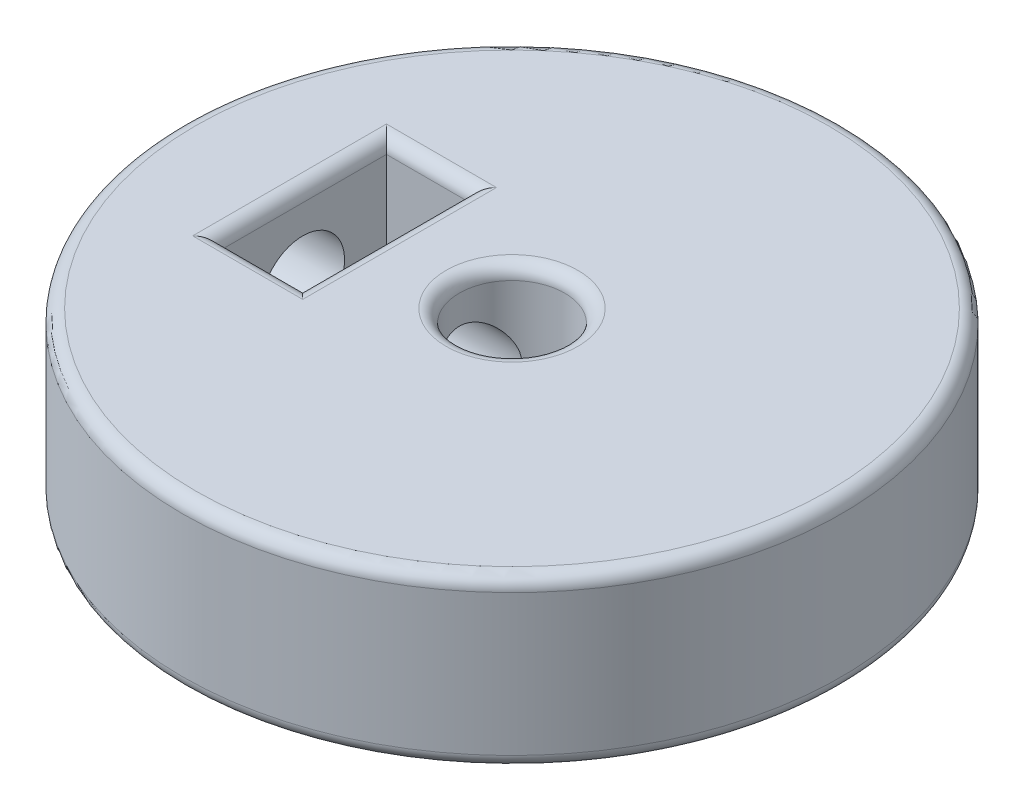
SolidWorks part; units mm, degrees
ref_plane "Front Plane" through (0, 0, 0) normal (0, 0, 1) x (1, 0, 0)
ref_plane "Top Plane" through (0, 0, 0) normal (0, 1, 0) x (1, 0, 0)
ref_plane "Right Plane" through (0, 0, 0) normal (1, 0, 0) x (0, 0, -1)
sketch "Sketch1" plane through (0, 0, 0) normal (0, 1, 0) x (1, 0, 0)
  circle A0 centre (0, 0) radius 4
  circle A1 centre (0, 0) radius 25
  dimension "D1" = 8
  dimension "D2" = 50
extrude "Boss-Extrude1" add sketch "Sketch1" along normal blind 12.7
sketch "Sketch2" plane through (0, 12.7, 0) normal (0, 1, 0) x (1, 0, 0)
  line L1 (-15.875, 6.35) -> (-9.525, 6.35)
  line L2 (-15.875, 6.35) -> (-15.875, -6.35)
  line L3 (-15.875, -6.35) -> (-9.525, -6.35)
  line L4 (-9.525, 6.35) -> (-9.525, -6.35)
  line L5 (-15.875, 6.35) -> (-9.525, -6.35) construction
  line L6 (-15.875, -6.35) -> (-9.525, 6.35) construction
  point P4 (-12.7, 0)
  point P5 (0, 0)
  dimension "D1" = 6.35
  dimension "D2" = 12.7
  dimension "D3" = 12.7
extrude "Cut-Extrude1" cut sketch "Sketch2" against normal through all
sketch "Sketch3" plane through (-9.525, 0, 0) normal (-1, 0, 0) x (0, 0, 1)
  circle A0 centre (0, 6.35) radius 3.175
  point P2 (0, 0)
  dimension "D1" = 6.35
  dimension "D2" = 6.35
extrude "Cut-Extrude2" cut sketch "Sketch3" along normal through all and the other way up to next
fillet "Fillet1" radius 1 12 edges at (0, 0, 4) (0, 0, 25) (-9.525, 0, 0) (-12.7, 0, 6.35) (-15.875, 0, 0) (-12.7, 0, -6.35) (0, 12.7, 4) (0, 12.7, 25) (-12.7, 12.7, 6.35) (-9.525, 12.7, 0) (-12.7, 12.7, -6.35) (-15.875, 12.7, 0)
